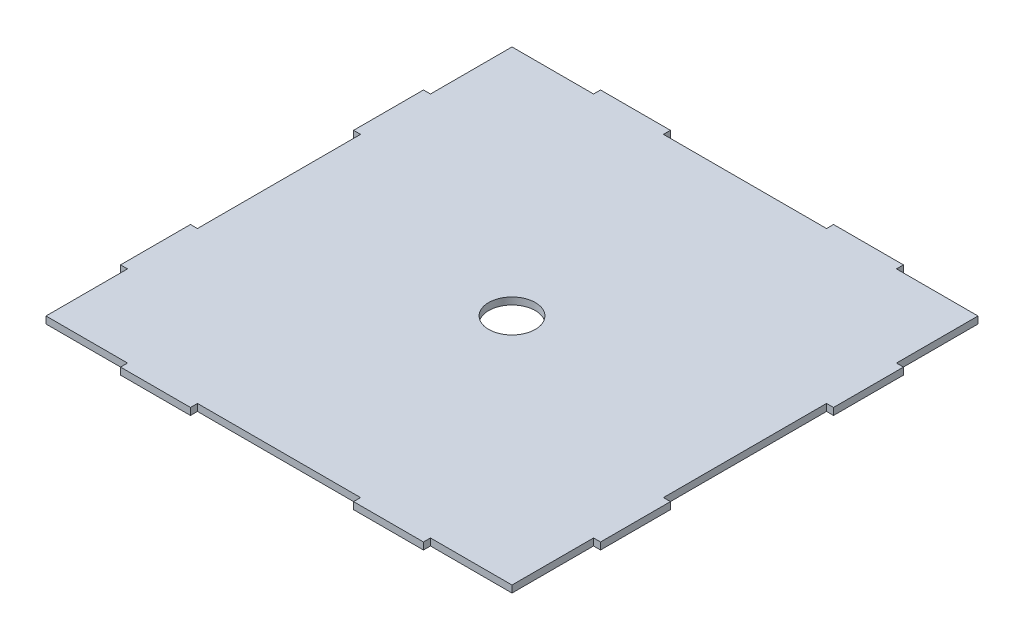
SolidWorks part; units mm, degrees
ref_plane "Front Plane" through (0, 0, 0) normal (0, 0, 1) x (1, 0, 0)
ref_plane "Top Plane" through (0, 0, 0) normal (0, 1, 0) x (1, 0, 0)
ref_plane "Right Plane" through (0, 0, 0) normal (1, 0, 0) x (0, 0, -1)
sketch "Sketch1" plane through (0, 0, 0) normal (0, 1, 0) x (1, 0, 0)
  line L1 (-100, 100) -> (100, 100)
  line L2 (-100, 100) -> (-100, -100)
  line L3 (-100, -100) -> (100, -100)
  line L4 (100, 100) -> (100, -100)
  line L5 (-100, 100) -> (100, -100) construction
  line L6 (-100, -100) -> (100, 100) construction
  point P0 (0, 0)
  dimension "D1" = 200
  dimension "D2" = 200
extrude "Boss-Extrude1" add sketch "Sketch1" along normal blind 3
sketch "Sketch2" plane through (0, 3, 0) normal (0, 1, 0) x (1, 0, 0)
  circle A0 centre (0, 0) radius 10
  dimension "D1" = 20
extrude "Cut-Extrude1" cut sketch "Sketch2" against normal blind 10
sketch "Sketch3" plane through (0, 3, 0) normal (0, 1, 0) x (1, 0, 0)
  line L0 (-100, 0) -> (100, 0) construction
  line L1 (-100, 100) -> (-100, -100) construction
  line L2 (100, -100) -> (100, 100) construction
  line L3 (0, 100) -> (0, -100) construction
  line L4 (100, 100) -> (-100, 100) construction
  line L5 (-100, -100) -> (100, -100) construction
  line L6 (100, 50) -> (103, 50) construction
  line L7 (100, 65) -> (103, 65)
  line L8 (100, 65) -> (100, 35)
  line L9 (100, 35) -> (103, 35)
  line L10 (103, 65) -> (103, 35)
  line L11 (100, -35) -> (103, -35)
  line L12 (103, -65) -> (103, -35)
  line L13 (100, -65) -> (103, -65)
  line L14 (100, -65) -> (100, -35)
  line L15 (65, -100) -> (35, -100)
  line L16 (65, -100) -> (65, -103)
  line L17 (65, -103) -> (35, -103)
  line L18 (35, -100) -> (35, -103)
  line L19 (-35, -100) -> (-35, -103)
  line L20 (-65, -103) -> (-35, -103)
  line L21 (-65, -100) -> (-65, -103)
  line L22 (-65, -100) -> (-35, -100)
  line L23 (-100, -65) -> (-100, -35)
  line L24 (-100, -65) -> (-103, -65)
  line L25 (-103, -65) -> (-103, -35)
  line L26 (-100, -35) -> (-103, -35)
  line L27 (-100, 35) -> (-103, 35)
  line L28 (-103, 65) -> (-103, 35)
  line L29 (-100, 65) -> (-103, 65)
  line L30 (-100, 65) -> (-100, 35)
  line L31 (-65, 100) -> (-35, 100)
  line L32 (-65, 100) -> (-65, 103)
  line L33 (-65, 103) -> (-35, 103)
  line L34 (-35, 100) -> (-35, 103)
  line L35 (35, 100) -> (35, 103)
  line L36 (65, 103) -> (35, 103)
  line L37 (65, 100) -> (65, 103)
  line L38 (65, 100) -> (35, 100)
  point P49 (0, 0)
  dimension "D1" = 30
  dimension "D2" = 3
  dimension "D3" = 50
  dimension "D4" = 4
extrude "Boss-Extrude2" add sketch "Sketch3" against normal blind 3
